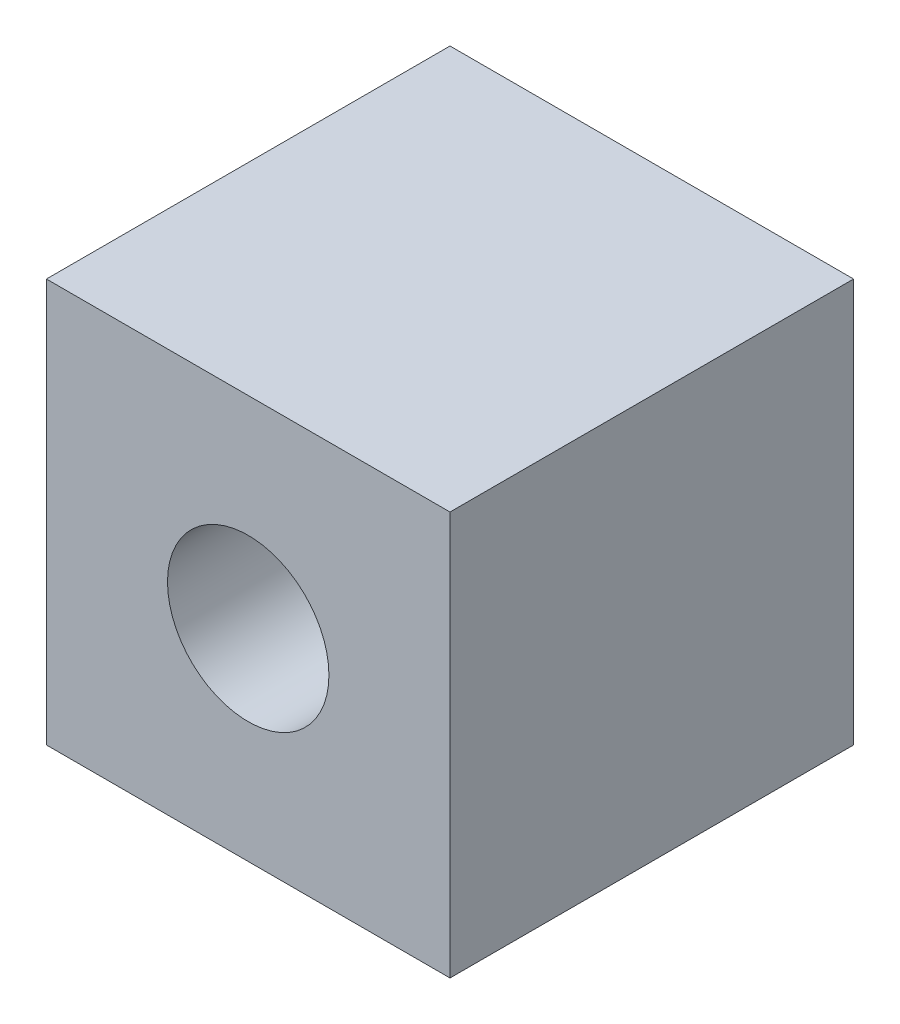
SolidWorks part; units mm, degrees
ref_plane "Front Plane" through (0, 0, 0) normal (0, 0, 1) x (1, 0, 0)
ref_plane "Top Plane" through (0, 0, 0) normal (0, 1, 0) x (1, 0, 0)
ref_plane "Right Plane" through (0, 0, 0) normal (1, 0, 0) x (0, 0, -1)
sketch "Sketch1" plane through (0, 0, 0) normal (0, 0, 1) x (1, 0, 0)
  line L1 (0, 0) -> (10, 0)
  line L2 (0, 0) -> (0, 10)
  line L3 (0, 10) -> (10, 10)
  line L4 (10, 0) -> (10, 10)
extrude "Boss-Extrude1" add sketch "Sketch1" along normal blind 10
sketch "Sketch2" plane through (0, 0, 0) normal (0, 0, 1) x (1, 0, 0)
  circle A0 centre (5, 5) radius 2
extrude "Cut-Extrude2" cut sketch "Sketch2" along normal through all
